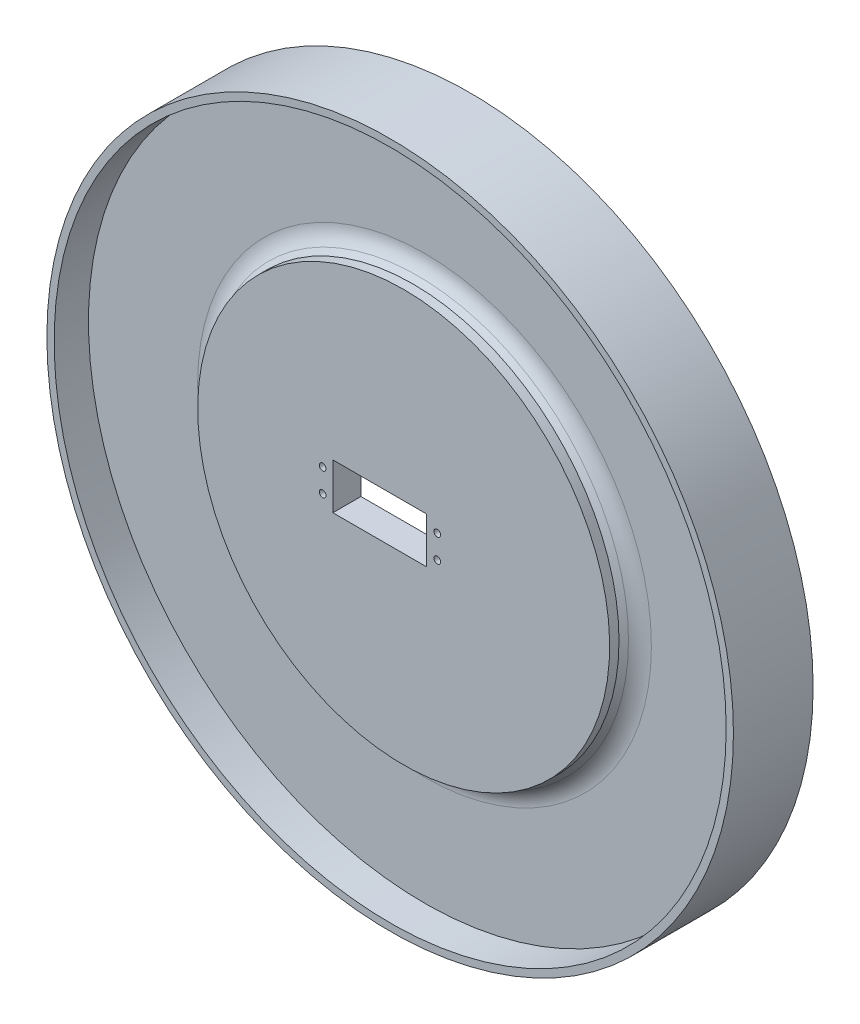
SolidWorks part; units mm, degrees
ref_plane "Front Plane" through (0, 0, 0) normal (0, 0, 1) x (1, 0, 0)
ref_plane "Top Plane" through (0, 0, 0) normal (0, 1, 0) x (1, 0, 0)
ref_plane "Right Plane" through (0, 0, 0) normal (1, 0, 0) x (0, 0, -1)
sketch "Sketch1" plane through (0, 0, 0) normal (0, 0, 1) x (1, 0, 0)
  circle A0 centre (0, 0) radius 150
  dimension "D1" = 300
extrude "Boss-Extrude1" add sketch "Sketch1" along normal mid plane 18.18
sketch "Sketch2" plane through (0, 0, 9.09) normal (0, 0, 1) x (1, 0, 0)
  circle A1 centre (0, 0) radius 146.82
  dimension "D2" = 293.64
extrude "Cut-Extrude1" cut sketch "Sketch2" against normal blind 15
sketch "Sketch5" plane through (0, 0, -5.91) normal (0, 0, 1) x (1, 0, 0)
  line L0 (0, 0) -> (0, 90) construction
  circle A0 centre (0, 0) radius 90
  dimension "D1" = 180
extrude "Boss-Extrude2" add sketch "Sketch5" along normal blind 15
chamfer "Chamfer1" distance 5 angle 45 1 edges at (90, 0, -5.91)
fillet "Fillet6" radius 10 1 edges at (95, 0, -5.91)
sketch "Sketch6" plane through (0, 0, 9.09) normal (0, 0, 1) x (1, 0, 0)
  line L0 (0, 0) -> (0, 77.6452) construction
  line L1 (64.65, 0) -> (-68.33, 0) construction
  line L2 (50.79, 24.14) -> (-54.47, 24.14) construction
  line L3 (50.79, -24.14) -> (50.79, 24.14) construction
  line L4 (-54.47, 24.14) -> (-54.47, -60.969) construction
  line L5 (50.79, -24.14) -> (-54.47, -24.14) construction
  circle A0 centre (64.65, 0) radius 1.55
  circle A1 centre (-68.33, 0) radius 1.55
  circle A2 centre (-54.47, 24.14) radius 1.55
  circle A3 centre (-54.47, -24.14) radius 1.55
  circle A4 centre (50.79, -24.14) radius 1.55
  circle A5 centre (50.79, 24.14) radius 1.55
  dimension "D1" = 3.1
  dimension "D2" = 64.65
  dimension "D3" = 48.28
  dimension "D4" = 13.86
  dimension "D5" = 48.28
  dimension "D6" = 13.86
  dimension "D7" = 68.33
extrude "Cut-Extrude2" cut sketch "Sketch6" against normal blind 5
sketch "Sketch7" plane through (0, 0, 9.09) normal (0, 0, 1) x (1, 0, 0)
  circle A0 centre (0, 0) radius 16
  dimension "D1" = 32
extrude "Cut-Extrude3" cut sketch "Sketch7" against normal blind 4.8
sketch "Sketch8" plane through (0, 0, 4.29) normal (0, 0, 1) x (1, 0, 0)
  line L0 (0, 0) -> (0, 20.0069) construction
  line L1 (0, 0) -> (-2.124, 20.208) construction
  line L2 (-0.7757, 14.9799) -> (-1.5657, 14.8969) construction
  circle A0 centre (0, 0) radius 14 construction
  circle A1 centre (0, 0) radius 15 construction
  circle A2 centre (0, 0) radius 14.095 construction
  arc A5 (1.3005, 15.9471) -> (0.4501, 13.9928) centre (6.2895, 12.6139) ccw
  arc A8 (0.4501, 13.9928) -> (-0.4501, 13.9928) centre (0, 0) ccw
  arc A9 (1.3005, 15.9471) -> (-1.3005, 15.9471) centre (0, 0) ccw
  circle A10 centre (0, 0) radius 16 construction
  arc A11 (-0.4501, 13.9928) -> (-1.3005, 15.9471) centre (-6.2895, 12.6139) ccw
  point P13 (0, 14)
  point P14 (0, 16)
  dimension "D1" = 28
  dimension "D2" = 28.19
  dimension "D3" = 30
  dimension "D4" = 6
  dimension "D5" = 0.79
  dimension "D6" = 6
extrude "Boss-Extrude3" add sketch "Sketch8" along normal up to surface (4.8 mm away) up to face at (16, 0, 9.09)
pattern_circular "CirPattern1" count 30 over 360 about axis through (0, 0, 0) along (0, 0, 1) of "Boss-Extrude3"
sketch "Sketch16" plane through (0, 0, 0) normal (1, 0, 0) x (0, 0, -1)
  line L1 (0, 88.5894) -> (4.2105, 88.5894)
  line L2 (0, 88.5894) -> (0, 80.1018)
  line L3 (0, 80.1018) -> (4.2105, 80.1018)
  line L4 (4.2105, 88.5894) -> (4.2105, 80.1018)
sketch "Sketch17" plane through (0, 0, 0) normal (1, 0, 0) x (0, 0, -1)
  line L1 (-3.18, 90) -> (-5.91, 90)
  line L2 (-3.18, 90) -> (-3.18, 0)
  line L3 (-3.18, 0) -> (-5.91, 0)
  line L4 (-5.91, 90) -> (-5.91, 0)
  line L7 (0.91, 0) -> (-43.906, 0) construction
  line L8 (0.91, 90) -> (0.91, -90) construction
  dimension "D1" = 2.73
  dimension "D2" = 90
  dimension "D3" = 3.18
revolve "Cut-Revolve4" cut sketch "Sketch17" angle 360 about L7
delete or keep bodies "Body-Delete/Keep 4" [suppressed] bodies 119
delete or keep bodies "Body-Delete/Keep 5" bodies 119
sketch "Sketch18" [suppressed] plane through (0, 0, 9.09) normal (0, 0, 1) x (1, 0, 0)
  circle A0 centre (0, 0) radius 16
sketch "Sketch23" plane through (0, 0, 3.18) normal (0, 0, 1) x (1, 0, 0)
  line L0 (0, 0) -> (-5.5293, 0) construction
  line L1 (-30.94, -10) -> (10.06, -10)
  line L2 (-30.94, -10) -> (-30.94, 10)
  line L3 (-30.94, 10) -> (10.06, 10)
  line L4 (10.06, -10) -> (10.06, 10)
  line L5 (-30.94, -10) -> (10.06, 10) construction
  line L6 (-30.94, 10) -> (10.06, -10) construction
  point P0 (-10.44, 0)
  point P5 (10.06, 0)
  dimension "D1" = 41
  dimension "D2" = 20
  dimension "D3" = 10.06
extrude "Cut-Extrude6" cut sketch "Sketch23" against normal through all
sketch "Sketch24" plane through (0, 0, 3.18) normal (0, 0, 1) x (1, 0, 0)
  line L0 (-35.4195, 5.08) -> (32.4034, 5.08) construction
  line L1 (-35.4195, 5.08) -> (-35.4195, -5.08) construction
  line L2 (14.6805, 5.08) -> (14.6805, -5.08) construction
  line L3 (-35.4195, -5.08) -> (14.6805, -5.08) construction
  line L4 (0, 0) -> (-17.3203, 0) construction
  circle A0 centre (-35.4195, -5.08) radius 1.47
  circle A1 centre (14.6805, -5.08) radius 1.47
  circle A2 centre (-35.4195, 5.08) radius 1.47
  circle A3 centre (14.6805, 5.08) radius 1.47
  dimension "D1" = 2.94
  dimension "D2" = 50.1
  dimension "D3" = 10.16
extrude "Cut-Extrude7" cut sketch "Sketch24" against normal through all and the other way through all
sketch "Sketch26" plane through (0, 0, -9.09) normal (0, 0, -1) x (-1, 0, 0)
  circle A0 centre (0, 0) radius 150
  circle A1 centre (0, 0) radius 120
  circle A2 centre (0, 0) radius 150 construction
  dimension "D1" = 30
extrude "Boss-Extrude4" add sketch "Sketch26" along normal blind 16.64
equation "\"module\"= 1"
equation "\"teeth\"= 10"
equation "\"pressureAngle\"= 20deg"
equation "\"gearThickness\"= 3.18"
equation "\"addendumFactor\"= 1"
equation "\"dedendumFactor\"= 1.25"
equation "\"pitch\"= 1 / \"module\""
equation "\"pitchDiameter\"= \"teeth\" / \"pitch\""
equation "\"addendum\"= \"addendumFactor\" / \"pitch\""
equation "\"dedendum\"= \"dedendumFactor\" / \"pitch\""
